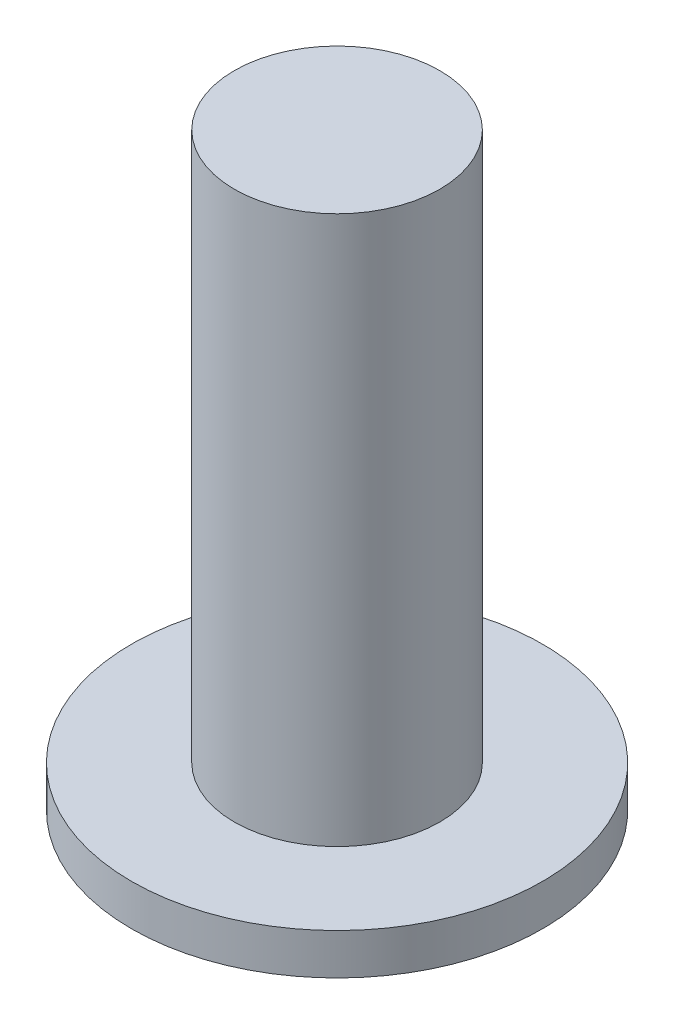
SolidWorks part; units mm, degrees
ref_plane "Front Plane" through (0, 0, 0) normal (0, 0, 1) x (1, 0, 0)
ref_plane "Top Plane" through (0, 0, 0) normal (0, 1, 0) x (1, 0, 0)
ref_plane "Right Plane" through (0, 0, 0) normal (1, 0, 0) x (0, 0, -1)
sketch "Sketch1" plane through (0, 0, 0) normal (0, 1, 0) x (1, 0, 0)
  circle A0 centre (0, 0) radius 150
  dimension "D1" = 300
extrude "Boss-Extrude1" add sketch "Sketch1" along normal blind 30
sketch "Sketch2" plane through (0, 30, 0) normal (0, 1, 0) x (1, 0, 0)
  circle A0 centre (0, 0) radius 75
  dimension "D1" = 150
extrude "Boss-Extrude2" add sketch "Sketch2" along normal blind 400
ref_plane "Plane1" through (0, 0, -75) normal (0, 0, -1) x (-1, 0, 0)
sketch "Sketch3" plane through (0, 0, -75) normal (0, 0, -1) x (-1, 0, 0)
  circle A0 centre (0, 354.9949) radius 50
  dimension "D1" = 100
extrude "Cut-Extrude1" cut sketch "Sketch3" against normal blind 100
